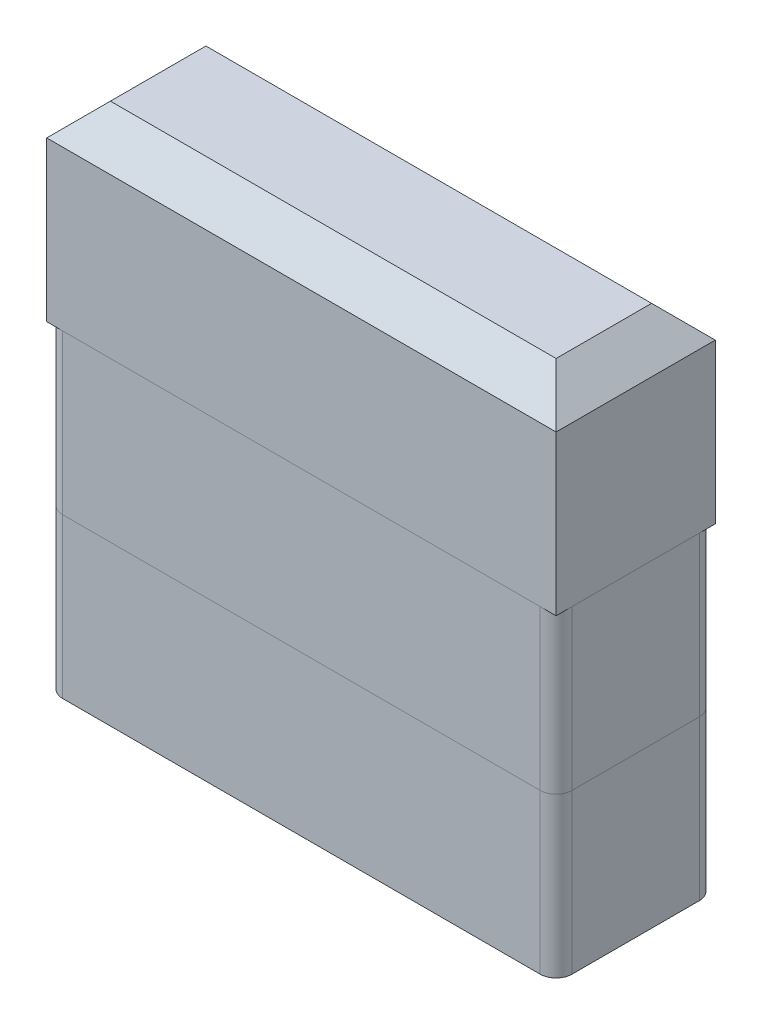
SolidWorks part; units mm, degrees
ref_plane "Front Plane" through (0, 0, 0) normal (0, 0, 1) x (1, 0, 0)
ref_plane "Top Plane" through (0, 0, 0) normal (0, 1, 0) x (1, 0, 0)
ref_plane "Right Plane" through (0, 0, 0) normal (1, 0, 0) x (0, 0, -1)
sketch "Sketch1" plane through (0, 0, 0) normal (0, 1, 0) x (1, 0, 0)
  line L1 (-80, -25) -> (80, -25)
  line L2 (-80, -25) -> (-80, 25)
  line L3 (-80, 25) -> (80, 25)
  line L4 (80, -25) -> (80, 25)
  line L5 (-80, -25) -> (80, 25) construction
  line L6 (-80, 25) -> (80, -25) construction
  point P0 (0, 0)
  dimension "D1" = 160
  dimension "D2" = 50
extrude "Boss-Extrude1" add sketch "Sketch1" along normal blind 160
chamfer "Chamfer1" distance 10 angle 45 4 edges at (0, 160, 25) (-80, 160, 0) (0, 160, -25) (80, 160, 0)
ref_plane "Plane1" through (0, 50, 0) normal (0, 1, 0) x (1, 0, 0)
ref_plane "Plane2" through (0, 100, 0) normal (0, 1, 0) x (1, 0, 0)
split "Split1" trim tools "Plane1" bodies to split 101 resulting bodies 103 104
split "Split2" trim tools "Plane2" bodies to split 103 resulting bodies 105 106
fillet "Fillet2" radius 5 4 edges at (-80, 25, -25) (-80, 25, 25) (80, 25, -25) (80, 25, 25)
fillet "Fillet3" radius 5 4 edges at (-80, 75, -25) (80, 75, -25) (80, 75, 25) (-80, 75, 25)
